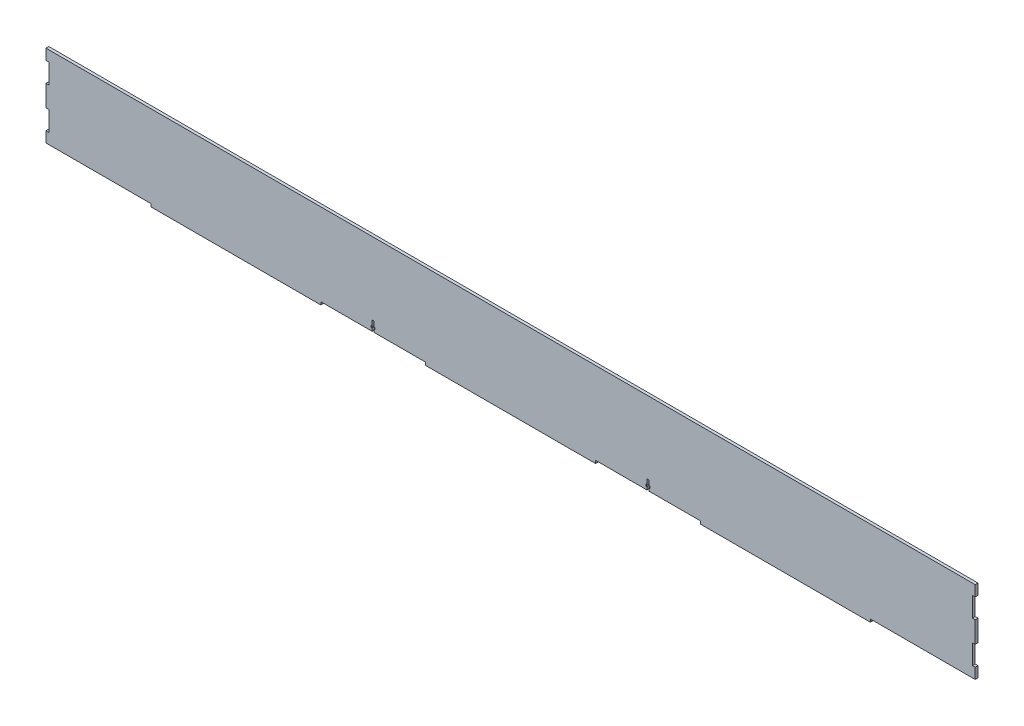
SolidWorks part; units mm, degrees
ref_plane "Alzado" through (0, 0, 0) normal (0, 0, 1) x (1, 0, 0)
ref_plane "Planta" through (0, 0, 0) normal (0, 1, 0) x (1, 0, 0)
ref_plane "Vista lateral" through (0, 0, 0) normal (1, 0, 0) x (0, 0, -1)
sketch "Croquis1" plane through (0, 0, 0) normal (0, 0, 1) x (1, 0, 0)
  line L0 (820, 0) -> (820, -363.7923) construction
  line L1 (0, 0) -> (185, 0)
  line L2 (0, 0) -> (0, 145)
  line L3 (0, 145) -> (1640, 145)
  line L4 (1640, 0) -> (1640, 145)
  line L5 (183.7346, 0) -> (185, 0)
  line L9 (485, -5) -> (185, -5)
  line L11 (670, 0) -> (670, -5)
  line L12 (670, -5) -> (970, -5)
  line L13 (970, 0) -> (970, -5)
  line L15 (1155, 0) -> (1155, -5)
  line L16 (1155, -5) -> (1455, -5)
  line L17 (1455, 0) -> (1455, -5)
  line L18 (185, 0) -> (185, -5)
  line L19 (485, 0) -> (481.1866, 0)
  line L20 (485, 0) -> (485, -5)
  line L21 (481.1866, 0) -> (670, 0)
  line L22 (970, 0) -> (1155, 0)
  line L23 (1455, 0) -> (1640, 0)
  point P15 (820, -5)
  dimension "D1" = 1640
  dimension "D2" = 145
  dimension "D3" = 5
  dimension "D4" = 185
  dimension "D5" = 300
  dimension "D6" = 300
  dimension "D7" = 5
  dimension "D8" = 185
extrude "Saliente-Extruir1" add sketch "Croquis1" along normal blind 5
sketch "Croquis2" plane through (0, 0, 5) normal (0, 0, 1) x (1, 0, 0)
  line L0 (1640, 72.5) -> (1561.7814, 72.5) construction
  line L1 (1640, 0) -> (1640, 145) construction
  line L2 (0, 145) -> (1640, 145) construction
  line L3 (1640, 126.25) -> (1635, 126.25)
  line L4 (1640, 126.25) -> (1640, 91.25)
  line L5 (1640, 91.25) -> (1635, 91.25)
  line L6 (1635, 126.25) -> (1635, 91.25)
  line L7 (1640, 53.75) -> (1635, 53.75)
  line L8 (1635, 18.75) -> (1635, 53.75)
  line L9 (1640, 18.75) -> (1635, 18.75)
  line L10 (1640, 18.75) -> (1640, 53.75)
  line L11 (820, 145) -> (820, 72.5) construction
  line L12 (0, 18.75) -> (0, 53.75)
  line L13 (0, 18.75) -> (5, 18.75)
  line L14 (5, 18.75) -> (5, 53.75)
  line L15 (0, 53.75) -> (5, 53.75)
  line L16 (0, 91.25) -> (5, 91.25)
  line L17 (5, 126.25) -> (5, 91.25)
  line L18 (0, 126.25) -> (5, 126.25)
  line L19 (0, 126.25) -> (0, 91.25)
  dimension "D1" = 35
  dimension "D2" = 18.75
  dimension "D3" = 5
extrude "Cortar-Extruir1" cut sketch "Croquis2" against normal blind 5 contours L7 L8 L9 L10 | L4 L3 L6 L5 | L16 L17 L18 L19 | L12 L15 L14 L13
sketch "Croquis3" plane through (0, 0, 5) normal (0, 0, 1) x (1, 0, 0)
  line L0 (577.5, 0) -> (577.5, 72.6456) construction
  line L1 (485, 0) -> (670, 0) construction
  line L2 (820, -5) -> (820, 72.6456) construction
  line L3 (670, -5) -> (970, -5) construction
  line L4 (579.3, 0) -> (575.7, 0)
  line L5 (575.7, 0) -> (575.7, 5)
  line L6 (575.7, 5) -> (573.9, 5)
  line L7 (573.9, 5) -> (573.9, 8.2)
  line L8 (573.9, 8.2) -> (575.7, 8.2)
  line L9 (575.7, 8.2) -> (575.7, 17.2)
  line L10 (575.7, 17.2) -> (579.3, 17.2)
  line L11 (579.3, 8.2) -> (579.3, 17.2)
  line L12 (581.1, 8.2) -> (579.3, 8.2)
  line L13 (581.1, 5) -> (581.1, 8.2)
  line L14 (579.3, 5) -> (581.1, 5)
  line L15 (579.3, 0) -> (579.3, 5)
  line L16 (1064.3, 8.2) -> (1064.3, 17.2)
  line L17 (1066.1, 8.2) -> (1064.3, 8.2)
  line L18 (1066.1, 5) -> (1066.1, 8.2)
  line L19 (1064.3, 5) -> (1066.1, 5)
  line L20 (1064.3, 0) -> (1064.3, 5)
  line L21 (1060.7, 0) -> (1064.3, 0)
  line L22 (1060.7, 0) -> (1060.7, 5)
  line L23 (1060.7, 5) -> (1058.9, 5)
  line L24 (1058.9, 5) -> (1058.9, 8.2)
  line L25 (1058.9, 8.2) -> (1060.7, 8.2)
  line L26 (1060.7, 8.2) -> (1060.7, 17.2)
  line L27 (1064.3, 17.2) -> (1060.7, 17.2)
  point P16 (577.5, 17.2)
  dimension "D1" = 1.8
  dimension "D2" = 5
  dimension "D3" = 1.8
  dimension "D4" = 3.2
  dimension "D5" = 1.8
  dimension "D6" = 9
extrude "Cortar-Extruir2" cut sketch "Croquis3" against normal blind 10 contours L10 L11 L12 L13 L14 L15 L4 L5 L6 L7 L8 L9 | L16 L27 L26 L25 L24 L23 L22 L21 L20 L19 L18 L17
